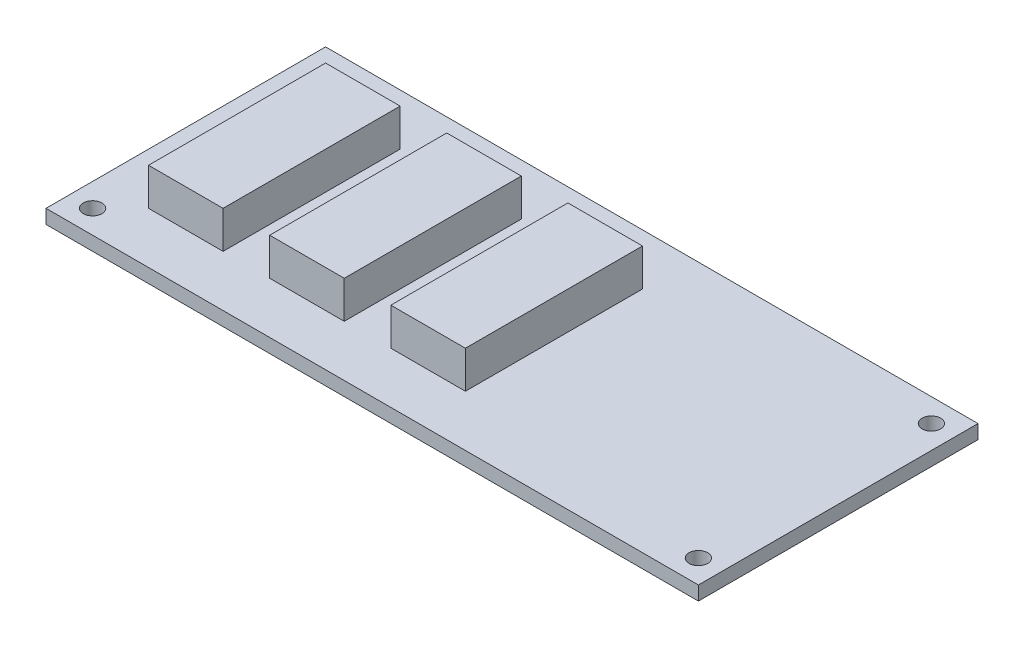
SolidWorks part; units mm, degrees
ref_plane "Front" through (0, 0, 0) normal (0, 0, 1) x (1, 0, 0)
ref_plane "Top" through (0, 0, 0) normal (0, 1, 0) x (1, 0, 0)
ref_plane "Right" through (0, 0, 0) normal (1, 0, 0) x (0, 0, -1)
sketch "Эскиз1" plane through (0, 0, 0) normal (0, 1, 0) x (1, 0, 0)
  line L0 (0, 15) -> (0, -15) construction
  line L1 (-35, 15) -> (35, 15)
  line L2 (-35, 15) -> (-35, -15)
  line L3 (-35, -15) -> (35, -15)
  line L4 (35, 15) -> (35, -15)
  line L5 (-35, 15) -> (35, -15) construction
  line L6 (-35, -15) -> (35, 15) construction
  line L7 (-35, 0) -> (35, 0) construction
  circle A0 centre (-32.5, 12.5) radius 1
  circle A1 centre (32.5, 12.5) radius 1
  circle A2 centre (32.5, -12.5) radius 1
  circle A3 centre (-32.5, -12.5) radius 1
  point P0 (0, 0)
  dimension "D3" = 2
  dimension "D4" = 25
  dimension "D1" = 30
  dimension "D2" = 70
  dimension "D5" = 65
extrude "Бобышка-Вытянуть1" add sketch "Эскиз1" along normal blind 1.5
sketch "Эскиз2" plane through (0, 1.5, 0) normal (0, 1, 0) x (1, 0, 0)
  line L0 (-35, 0) -> (35, 0) construction
  line L1 (-35, 15) -> (-35, -15) construction
  line L2 (35, -15) -> (35, 15) construction
  line L4 (-29.5, 9.5) -> (-21.5, 9.5)
  line L5 (-29.5, 9.5) -> (-29.5, -9.5)
  line L6 (-29.5, -9.5) -> (-21.5, -9.5)
  line L7 (-21.5, 9.5) -> (-21.5, -9.5)
  line L8 (-29.5, 9.5) -> (-21.5, -9.5) construction
  line L9 (-29.5, -9.5) -> (-21.5, 9.5) construction
  line L10 (-16.5, 9.5) -> (-8.5, 9.5)
  line L11 (-16.5, 9.5) -> (-16.5, -9.5)
  line L12 (-16.5, -9.5) -> (-8.5, -9.5)
  line L13 (-8.5, 9.5) -> (-8.5, -9.5)
  line L14 (-16.5, 9.5) -> (-8.5, -9.5) construction
  line L15 (-16.5, -9.5) -> (-8.5, 9.5) construction
  line L16 (-3.5, 9.5) -> (4.5, 9.5)
  line L17 (-3.5, 9.5) -> (-3.5, -9.5)
  line L18 (-3.5, -9.5) -> (4.5, -9.5)
  line L19 (4.5, 9.5) -> (4.5, -9.5)
  line L20 (-3.5, 9.5) -> (4.5, -9.5) construction
  line L21 (-3.5, -9.5) -> (4.5, 9.5) construction
  point P6 (-25.5, 0)
  point P11 (-12.5, 0)
  point P16 (0.5, 0)
  dimension "D1" = 8
  dimension "D2" = 19
  dimension "D3" = 5.5
  dimension "D4" = 26.5
  dimension "D5" = 39.5
extrude "Бобышка-Вытянуть2" add sketch "Эскиз2" along normal blind 4
